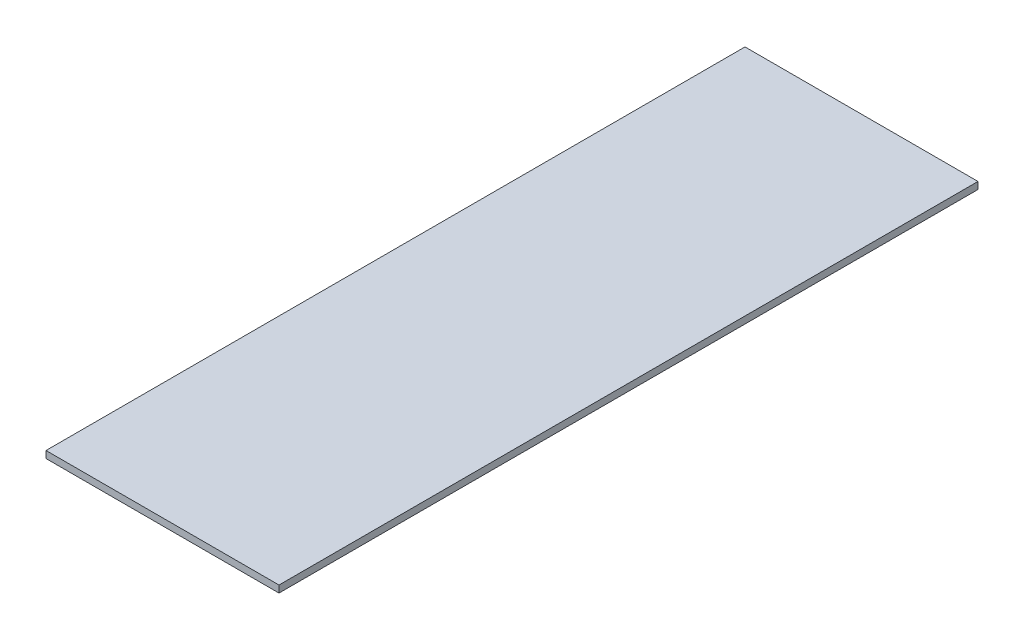
SolidWorks part; units mm, degrees
material "6061 Alloy"
ref_plane "Front Plane" through (0, 0, 0) normal (0, 0, 1) x (1, 0, 0)
ref_plane "Top Plane" through (0, 0, 0) normal (0, 1, 0) x (1, 0, 0)
ref_plane "Right Plane" through (0, 0, 0) normal (1, 0, 0) x (0, 0, -1)
sketch "Sketch1" plane through (0, 0, 0) normal (0, 1, 0) x (1, 0, 0)
  line L1 (-50, -150) -> (50, -150)
  line L2 (-50, -150) -> (-50, 150)
  line L3 (-50, 150) -> (50, 150)
  line L4 (50, -150) -> (50, 150)
  line L5 (-50, -150) -> (50, 150) construction
  line L6 (-50, 150) -> (50, -150) construction
  point P0 (0, 0)
  dimension "D1" = 100
  dimension "D2" = 300
extrude "Boss-Extrude1" add sketch "Sketch1" along normal blind 3
